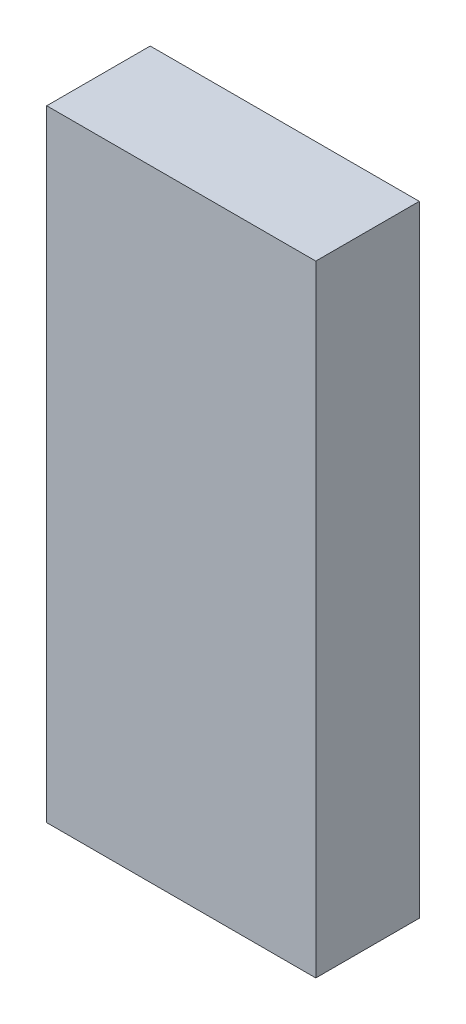
SolidWorks part; units mm, degrees
ref_plane "Front Plane" through (0, 0, 0) normal (0, 0, 1) x (1, 0, 0)
ref_plane "Top Plane" through (0, 0, 0) normal (0, 1, 0) x (1, 0, 0)
ref_plane "Right Plane" through (0, 0, 0) normal (1, 0, 0) x (0, 0, -1)
sketch "Sketch1" plane through (0, 0, 0) normal (0, 1, 0) x (1, 0, 0)
  line L1 (-41.2811, 0.8394) -> (23.7189, 0.8394)
  line L2 (-41.2811, 0.8394) -> (-41.2811, -24.1606)
  line L3 (-41.2811, -24.1606) -> (23.7189, -24.1606)
  line L4 (23.7189, 0.8394) -> (23.7189, -24.1606)
extrude "Boss-Extrude1" add sketch "Sketch1" along normal blind 150
